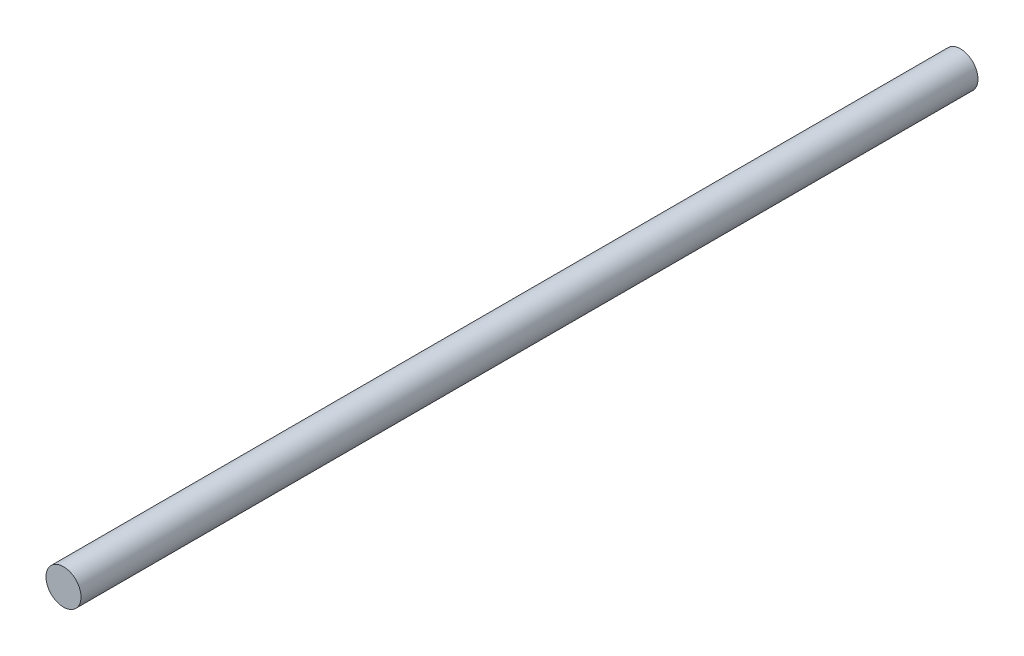
SolidWorks part; units mm, degrees
ref_plane "Front Plane" through (0, 0, 0) normal (0, 0, 1) x (1, 0, 0)
ref_plane "Top Plane" through (0, 0, 0) normal (0, 1, 0) x (1, 0, 0)
ref_plane "Right Plane" through (0, 0, 0) normal (1, 0, 0) x (0, 0, -1)
sketch "Sketch1" plane through (0, 0, 0) normal (0, 0, 1) x (1, 0, 0)
  circle A0 centre (0, 0) radius 12.7
  dimension "D1" = 25.4
extrude "Boss-Extrude1" add sketch "Sketch1" along normal blind 650
